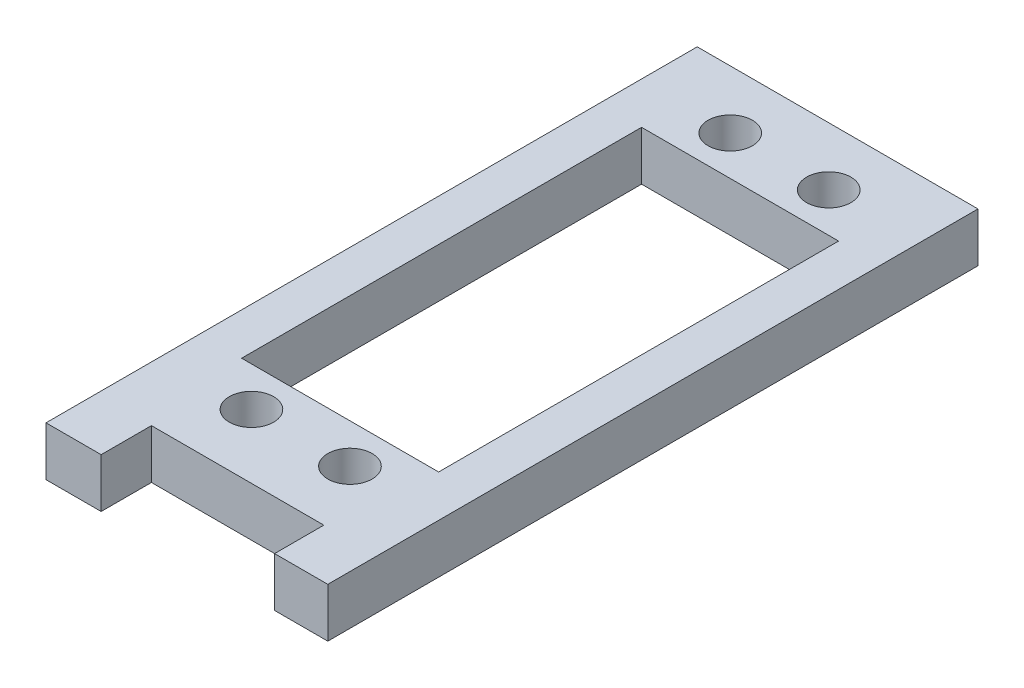
SolidWorks part; units mm, degrees
ref_plane "Front Plane" through (0, 0, 0) normal (0, 0, 1) x (1, 0, 0)
ref_plane "Top Plane" through (0, 0, 0) normal (0, 1, 0) x (1, 0, 0)
ref_plane "Right Plane" through (0, 0, 0) normal (1, 0, 0) x (0, 0, -1)
sketch "Sketch1" plane through (0, 0, 0) normal (0, 1, 0) x (1, 0, 0)
  line L0 (0, 0) -> (20, -40.6) construction
  line L1 (0, 0) -> (20, 0)
  line L2 (0, 0) -> (0, -40.6)
  line L3 (0, -40.6) -> (20, -40.6)
  line L4 (20, 0) -> (20, -40.6)
  line L5 (20, -40.6) -> (20.2313, -40.5167) construction
  line L6 (0, -40.6) -> (20, 0) construction
  line L7 (24.25, -20.3) -> (-4.25, -20.3) construction
  line L8 (-4.25, -48) -> (24.25, -48) construction
  line L9 (-4.25, -48) -> (-4.25, 7.4)
  line L11 (24.25, -48) -> (24.25, 7.4)
  line L12 (-4.25, -48) -> (24.25, 7.4) construction
  line L13 (-4.25, 7.4) -> (24.25, -48) construction
  line L14 (-4.25, -48) -> (24.25, -48) construction
  line L15 (-4.25, -48) -> (-4.25, -56.2048)
  line L17 (24.25, -48) -> (24.25, -56.1)
  line L18 (19.5394, -48) -> (0.4606, -48) construction
  line L19 (1.3481, -56.2048) -> (-4.25, -56.2048)
  line L21 (1.3481, -56.2048) -> (1.3481, -51.1)
  line L22 (10, 0) -> (10, -48) construction
  line L23 (1.3481, -51.1) -> (18.8481, -51.1)
  line L24 (18.8481, -56.1) -> (18.8481, -51.1)
  line L25 (1.3481, -56.2048) -> (18.8481, -51.1) construction
  line L26 (1.3481, -51.1) -> (18.8481, -56.1) construction
  line L27 (18.8481, -56.1) -> (24.25, -56.1)
  line L28 (-4.25, 7.4) -> (-4.25, 9.9)
  line L29 (-4.25, 9.9) -> (24.25, 9.9)
  line L30 (24.25, 7.4) -> (24.25, 9.9)
  circle A0 centre (5, 4) radius 2.25
  circle A1 centre (15, 4) radius 2.25
  circle A2 centre (5, -44.6) radius 2.25
  circle A3 centre (15, -44.6) radius 2.25
  point P4 (10, -20.3)
  point P14 (10.1889, -53.6259)
  dimension "D6" = 4.5
  dimension "D1" = 40.6
  dimension "D2" = 20
  dimension "D3" = 55.4
  dimension "D4" = 5
  dimension "D5" = 17.5
  dimension "D7" = 10
  dimension "D8" = 48.6
  dimension "D9" = 28.5
  dimension "D10" = 2.5
extrude "Boss-Extrude1" add sketch "Sketch1" along normal blind 5
